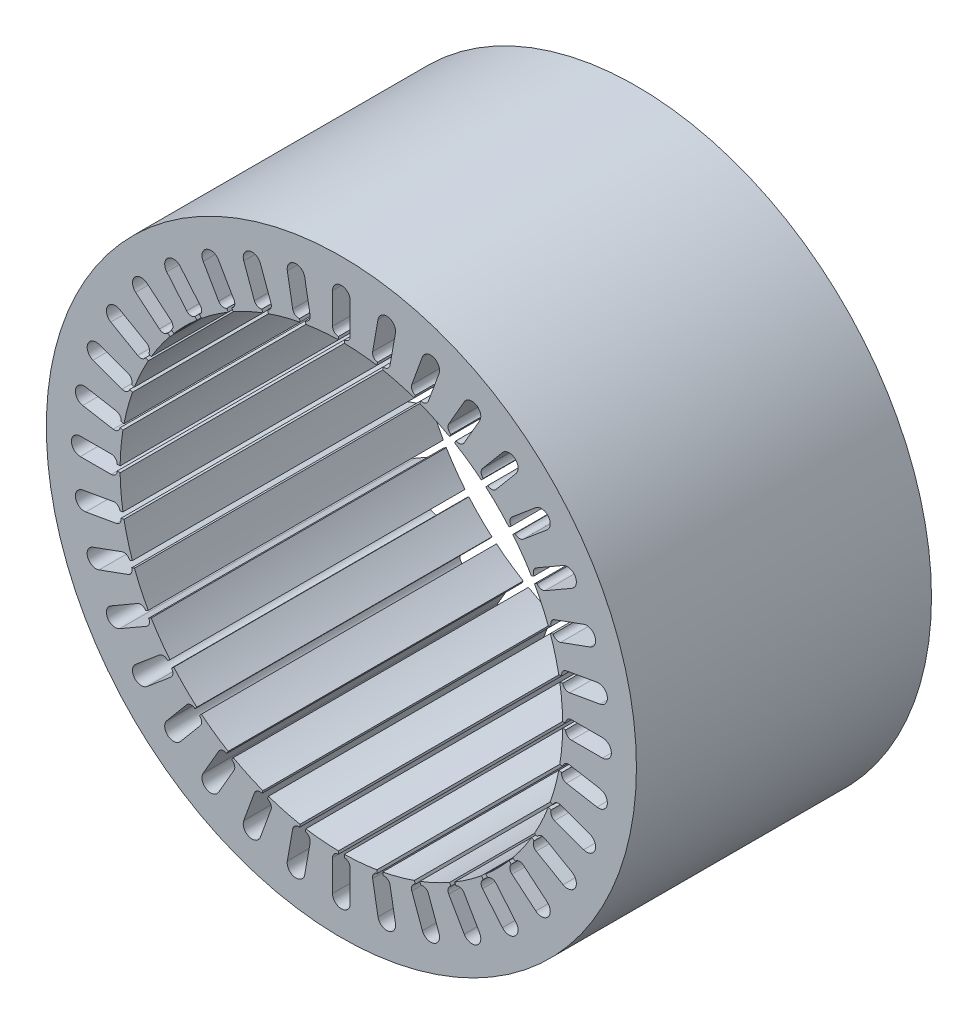
SolidWorks part; units mm, degrees
ref_plane "Front Plane" through (0, 0, 0) normal (0, 0, 1) x (1, 0, 0)
ref_plane "Top Plane" through (0, 0, 0) normal (0, 1, 0) x (1, 0, 0)
ref_plane "Right Plane" through (0, 0, 0) normal (1, 0, 0) x (0, 0, -1)
sketch "Sketch1" plane through (0, 0, 0) normal (0, 0, 1) x (1, 0, 0)
  line L0 (0, 0) -> (98.434, 0) construction
  line L1 (74.0277, -12.0376) -> (75.0125, -12.2113)
  line L2 (77.3294, -10.589) -> (87.6699, -12.4123)
  line L3 (76.2875, -16.4978) -> (86.628, -18.3211)
  line L4 (73.6804, -14.0073) -> (74.6652, -14.1809)
  line L5 (70.8127, -24.7095) -> (71.7524, -25.0516)
  line L6 (74.3158, -23.8562) -> (84.1826, -27.4474)
  line L7 (0, 0) -> (98.8022, 8.6441) construction
  line L8 (74.9933, 1) -> (75.9933, 1)
  line L9 (77.9933, 3) -> (88.4933, 3)
  line L10 (77.9933, -3) -> (88.4933, -3)
  line L11 (74.9933, -1) -> (75.9933, -1)
  line L12 (72.2637, -29.4944) -> (82.1305, -33.0856)
  line L13 (70.1287, -26.5889) -> (71.0684, -26.9309)
  line L14 (65.4461, -36.6306) -> (66.3122, -37.1306)
  line L15 (69.0442, -36.3986) -> (78.1375, -41.6486)
  line L16 (66.0442, -41.5947) -> (75.1375, -46.8447)
  line L17 (64.4461, -38.3627) -> (65.3122, -38.8627)
  line L18 (58.091, -47.4387) -> (58.8571, -48.0815)
  line L19 (61.6747, -47.835) -> (69.7182, -54.5843)
  line L20 (57.818, -52.4313) -> (65.8615, -59.1806)
  line L21 (56.8054, -48.9708) -> (57.5715, -49.6136)
  line L22 (48.9708, -56.8054) -> (49.6136, -57.5715)
  line L23 (52.4313, -57.818) -> (59.1806, -65.8615)
  line L24 (47.835, -61.6747) -> (54.5843, -69.7182)
  line L25 (47.4387, -58.091) -> (48.0815, -58.8571)
  line L26 (38.3627, -64.4461) -> (38.8627, -65.3122)
  line L27 (41.5947, -66.0442) -> (46.8447, -75.1375)
  line L28 (36.3986, -69.0442) -> (41.6486, -78.1375)
  line L29 (36.6306, -65.4461) -> (37.1306, -66.3122)
  line L30 (26.5889, -70.1287) -> (26.9309, -71.0684)
  line L31 (29.4944, -72.2637) -> (33.0856, -82.1305)
  line L32 (23.8562, -74.3158) -> (27.4474, -84.1826)
  line L33 (24.7095, -70.8127) -> (25.0516, -71.7524)
  line L34 (14.0073, -73.6804) -> (14.1809, -74.6652)
  line L35 (16.4978, -76.2875) -> (18.3211, -86.628)
  line L36 (10.589, -77.3294) -> (12.4123, -87.6699)
  line L37 (12.0376, -74.0277) -> (12.2113, -75.0125)
  line L38 (1, -74.9933) -> (1, -75.9933)
  line L39 (3, -77.9933) -> (3, -88.4933)
  line L40 (-3, -77.9933) -> (-3, -88.4933)
  line L41 (-1, -74.9933) -> (-1, -75.9933)
  line L42 (-12.0376, -74.0277) -> (-12.2113, -75.0125)
  line L43 (-10.589, -77.3294) -> (-12.4123, -87.6699)
  line L44 (-16.4978, -76.2875) -> (-18.3211, -86.628)
  line L45 (-14.0073, -73.6804) -> (-14.1809, -74.6652)
  line L46 (-24.7095, -70.8127) -> (-25.0516, -71.7524)
  line L47 (-23.8562, -74.3158) -> (-27.4474, -84.1826)
  line L48 (-29.4944, -72.2637) -> (-33.0856, -82.1305)
  line L49 (-26.5889, -70.1287) -> (-26.9309, -71.0684)
  line L50 (-36.6306, -65.4461) -> (-37.1306, -66.3122)
  line L51 (-36.3986, -69.0442) -> (-41.6486, -78.1375)
  line L52 (-41.5947, -66.0442) -> (-46.8447, -75.1375)
  line L53 (-38.3627, -64.4461) -> (-38.8627, -65.3122)
  line L54 (-47.4387, -58.091) -> (-48.0815, -58.8571)
  line L55 (-47.835, -61.6747) -> (-54.5843, -69.7182)
  line L56 (-52.4313, -57.818) -> (-59.1806, -65.8615)
  line L57 (-48.9708, -56.8054) -> (-49.6136, -57.5715)
  line L58 (-56.8054, -48.9708) -> (-57.5715, -49.6136)
  line L59 (-57.818, -52.4313) -> (-65.8615, -59.1806)
  line L60 (-61.6747, -47.835) -> (-69.7182, -54.5843)
  line L61 (-58.091, -47.4387) -> (-58.8571, -48.0815)
  line L62 (-64.4461, -38.3627) -> (-65.3122, -38.8627)
  line L63 (-66.0442, -41.5947) -> (-75.1375, -46.8447)
  line L64 (-69.0442, -36.3986) -> (-78.1375, -41.6486)
  line L65 (-65.4461, -36.6306) -> (-66.3122, -37.1306)
  line L66 (-70.1287, -26.5889) -> (-71.0684, -26.9309)
  line L67 (-72.2637, -29.4944) -> (-82.1305, -33.0856)
  line L68 (-74.3158, -23.8562) -> (-84.1826, -27.4474)
  line L69 (-70.8127, -24.7095) -> (-71.7524, -25.0516)
  line L70 (-73.6804, -14.0073) -> (-74.6652, -14.1809)
  line L71 (-76.2875, -16.4978) -> (-86.628, -18.3211)
  line L72 (-77.3294, -10.589) -> (-87.6699, -12.4123)
  line L73 (-74.0277, -12.0376) -> (-75.0125, -12.2113)
  line L74 (-74.9933, -1) -> (-75.9933, -1)
  line L75 (-77.9933, -3) -> (-88.4933, -3)
  line L76 (-77.9933, 3) -> (-88.4933, 3)
  line L77 (-74.9933, 1) -> (-75.9933, 1)
  line L78 (-74.0277, 12.0376) -> (-75.0125, 12.2113)
  line L79 (-77.3294, 10.589) -> (-87.6699, 12.4123)
  line L80 (-76.2875, 16.4978) -> (-86.628, 18.3211)
  line L81 (-73.6804, 14.0073) -> (-74.6652, 14.1809)
  line L82 (-70.8127, 24.7095) -> (-71.7524, 25.0516)
  line L83 (-74.3158, 23.8562) -> (-84.1826, 27.4474)
  line L84 (-72.2637, 29.4944) -> (-82.1305, 33.0856)
  line L85 (-70.1287, 26.5889) -> (-71.0684, 26.9309)
  line L86 (-65.4461, 36.6306) -> (-66.3122, 37.1306)
  line L87 (-69.0442, 36.3986) -> (-78.1375, 41.6486)
  line L88 (-66.0442, 41.5947) -> (-75.1375, 46.8447)
  line L89 (-64.4461, 38.3627) -> (-65.3122, 38.8627)
  line L90 (-58.091, 47.4387) -> (-58.8571, 48.0815)
  line L91 (-61.6747, 47.835) -> (-69.7182, 54.5843)
  line L92 (-57.818, 52.4313) -> (-65.8615, 59.1806)
  line L93 (-56.8054, 48.9708) -> (-57.5715, 49.6136)
  line L94 (-48.9708, 56.8054) -> (-49.6136, 57.5715)
  line L95 (-52.4313, 57.818) -> (-59.1806, 65.8615)
  line L96 (-47.835, 61.6747) -> (-54.5843, 69.7182)
  line L97 (-47.4387, 58.091) -> (-48.0815, 58.8571)
  line L98 (-38.3627, 64.4461) -> (-38.8627, 65.3122)
  line L99 (-41.5947, 66.0442) -> (-46.8447, 75.1375)
  line L100 (-36.3986, 69.0442) -> (-41.6486, 78.1375)
  line L101 (-36.6306, 65.4461) -> (-37.1306, 66.3122)
  line L102 (-26.5889, 70.1287) -> (-26.9309, 71.0684)
  line L103 (-29.4944, 72.2637) -> (-33.0856, 82.1305)
  line L104 (-23.8562, 74.3158) -> (-27.4474, 84.1826)
  line L105 (-24.7095, 70.8127) -> (-25.0516, 71.7524)
  line L106 (-14.0073, 73.6804) -> (-14.1809, 74.6652)
  line L107 (-16.4978, 76.2875) -> (-18.3211, 86.628)
  line L108 (-10.589, 77.3294) -> (-12.4123, 87.6699)
  line L109 (-12.0376, 74.0277) -> (-12.2113, 75.0125)
  line L110 (-1, 74.9933) -> (-1, 75.9933)
  line L111 (-3, 77.9933) -> (-3, 88.4933)
  line L112 (3, 77.9933) -> (3, 88.4933)
  line L113 (1, 74.9933) -> (1, 75.9933)
  line L114 (12.0376, 74.0277) -> (12.2113, 75.0125)
  line L115 (10.589, 77.3294) -> (12.4123, 87.6699)
  line L116 (16.4978, 76.2875) -> (18.3211, 86.628)
  line L117 (14.0073, 73.6804) -> (14.1809, 74.6652)
  line L118 (24.7095, 70.8127) -> (25.0516, 71.7524)
  line L119 (23.8562, 74.3158) -> (27.4474, 84.1826)
  line L120 (29.4944, 72.2637) -> (33.0856, 82.1305)
  line L121 (26.5889, 70.1287) -> (26.9309, 71.0684)
  line L122 (36.6306, 65.4461) -> (37.1306, 66.3122)
  line L123 (36.3986, 69.0442) -> (41.6486, 78.1375)
  line L124 (41.5947, 66.0442) -> (46.8447, 75.1375)
  line L125 (38.3627, 64.4461) -> (38.8627, 65.3122)
  line L126 (47.4387, 58.091) -> (48.0815, 58.8571)
  line L127 (47.835, 61.6747) -> (54.5843, 69.7182)
  line L128 (52.4313, 57.818) -> (59.1806, 65.8615)
  line L129 (48.9708, 56.8054) -> (49.6136, 57.5715)
  line L130 (56.8054, 48.9708) -> (57.5715, 49.6136)
  line L131 (57.818, 52.4313) -> (65.8615, 59.1806)
  line L132 (61.6747, 47.835) -> (69.7182, 54.5843)
  line L133 (58.091, 47.4387) -> (58.8571, 48.0815)
  line L134 (64.4461, 38.3627) -> (65.3122, 38.8627)
  line L135 (66.0442, 41.5947) -> (75.1375, 46.8447)
  line L136 (69.0442, 36.3986) -> (78.1375, 41.6486)
  line L137 (65.4461, 36.6306) -> (66.3122, 37.1306)
  line L138 (70.1287, 26.5889) -> (71.0684, 26.9309)
  line L139 (72.2637, 29.4944) -> (82.1305, 33.0856)
  line L140 (74.3158, 23.8562) -> (84.1826, 27.4474)
  line L141 (70.8127, 24.7095) -> (71.7524, 25.0516)
  line L142 (73.6804, 14.0073) -> (74.6652, 14.1809)
  line L143 (76.2875, 16.4978) -> (86.628, 18.3211)
  line L144 (77.3294, 10.589) -> (87.6699, 12.4123)
  line L145 (74.0277, 12.0376) -> (75.0125, 12.2113)
  arc A0 (75.9933, 1) -> (77.9933, 3) centre (77.9933, 1) cw
  arc A1 (88.4933, 3) -> (88.4933, -3) centre (88.4933, 0) cw
  arc A2 (75.9933, -1) -> (77.9933, -3) centre (77.9933, -1) ccw
  arc A3 (74.9933, 1) -> (74.7146, 6.5367) centre (0, 0) ccw
  arc A4 (74.9933, -1) -> (74.7146, -6.5367) centre (0, 0) cw
  arc A5 (74.0277, -12.0376) -> (74.7146, -6.5367) centre (0, 0) ccw
  arc A6 (75.0125, -12.2113) -> (77.3294, -10.589) centre (76.9821, -12.5586) cw
  arc A7 (87.6699, -12.4123) -> (86.628, -18.3211) centre (87.1489, -15.3667) cw
  arc A8 (74.6652, -14.1809) -> (76.2875, -16.4978) centre (76.6348, -14.5282) ccw
  arc A9 (73.6804, -14.0073) -> (72.4444, -19.4114) centre (0, 0) cw
  arc A10 (70.8127, -24.7095) -> (72.4444, -19.4114) centre (0, 0) ccw
  arc A11 (71.7524, -25.0516) -> (74.3158, -23.8562) centre (73.6318, -25.7356) cw
  arc A12 (84.1826, -27.4474) -> (82.1305, -33.0856) centre (83.1565, -30.2665) cw
  arc A13 (71.0684, -26.9309) -> (72.2637, -29.4944) centre (72.9477, -27.615) ccw
  arc A14 (70.1287, -26.5889) -> (67.9731, -31.6964) centre (0, 0) cw
  arc A15 (65.4461, -36.6306) -> (67.9731, -31.6964) centre (0, 0) ccw
  arc A16 (66.3122, -37.1306) -> (69.0442, -36.3986) centre (68.0442, -38.1306) cw
  arc A17 (78.1375, -41.6486) -> (75.1375, -46.8447) centre (76.6375, -44.2467) cw
  arc A18 (65.3122, -38.8627) -> (66.0442, -41.5947) centre (67.0442, -39.8627) ccw
  arc A19 (64.4461, -38.3627) -> (61.4364, -43.0182) centre (0, 0) cw
  arc A20 (58.091, -47.4387) -> (61.4364, -43.0182) centre (0, 0) ccw
  arc A21 (58.8571, -48.0815) -> (61.6747, -47.835) centre (60.3891, -49.3671) cw
  arc A22 (69.7182, -54.5843) -> (65.8615, -59.1806) centre (67.7898, -56.8824) cw
  arc A23 (57.5715, -49.6136) -> (57.818, -52.4313) centre (59.1036, -50.8992) ccw
  arc A24 (56.8054, -48.9708) -> (53.033, -53.033) centre (0, 0) cw
  arc A25 (48.9708, -56.8054) -> (53.033, -53.033) centre (0, 0) ccw
  arc A26 (49.6136, -57.5715) -> (52.4313, -57.818) centre (50.8992, -59.1036) cw
  arc A27 (59.1806, -65.8615) -> (54.5843, -69.7182) centre (56.8824, -67.7898) cw
  arc A28 (48.0815, -58.8571) -> (47.835, -61.6747) centre (49.3671, -60.3891) ccw
  arc A29 (47.4387, -58.091) -> (43.0182, -61.4364) centre (0, 0) cw
  arc A30 (38.3627, -64.4461) -> (43.0182, -61.4364) centre (0, 0) ccw
  arc A31 (38.8627, -65.3122) -> (41.5947, -66.0442) centre (39.8627, -67.0442) cw
  arc A32 (46.8447, -75.1375) -> (41.6486, -78.1375) centre (44.2467, -76.6375) cw
  arc A33 (37.1306, -66.3122) -> (36.3986, -69.0442) centre (38.1306, -68.0442) ccw
  arc A34 (36.6306, -65.4461) -> (31.6964, -67.9731) centre (0, 0) cw
  arc A35 (26.5889, -70.1287) -> (31.6964, -67.9731) centre (0, 0) ccw
  arc A36 (26.9309, -71.0684) -> (29.4944, -72.2637) centre (27.615, -72.9477) cw
  arc A37 (33.0856, -82.1305) -> (27.4474, -84.1826) centre (30.2665, -83.1565) cw
  arc A38 (25.0516, -71.7524) -> (23.8562, -74.3158) centre (25.7356, -73.6318) ccw
  arc A39 (24.7095, -70.8127) -> (19.4114, -72.4444) centre (0, 0) cw
  arc A40 (14.0073, -73.6804) -> (19.4114, -72.4444) centre (0, 0) ccw
  arc A41 (14.1809, -74.6652) -> (16.4978, -76.2875) centre (14.5282, -76.6348) cw
  arc A42 (18.3211, -86.628) -> (12.4123, -87.6699) centre (15.3667, -87.1489) cw
  arc A43 (12.2113, -75.0125) -> (10.589, -77.3294) centre (12.5586, -76.9821) ccw
  arc A44 (12.0376, -74.0277) -> (6.5367, -74.7146) centre (0, 0) cw
  arc A45 (1, -74.9933) -> (6.5367, -74.7146) centre (0, 0) ccw
  arc A46 (1, -75.9933) -> (3, -77.9933) centre (1, -77.9933) cw
  arc A47 (3, -88.4933) -> (-3, -88.4933) centre (0, -88.4933) cw
  arc A48 (-1, -75.9933) -> (-3, -77.9933) centre (-1, -77.9933) ccw
  arc A49 (-1, -74.9933) -> (-6.5367, -74.7146) centre (0, 0) cw
  arc A50 (-12.0376, -74.0277) -> (-6.5367, -74.7146) centre (0, 0) ccw
  arc A51 (-12.2113, -75.0125) -> (-10.589, -77.3294) centre (-12.5586, -76.9821) cw
  arc A52 (-12.4123, -87.6699) -> (-18.3211, -86.628) centre (-15.3667, -87.1489) cw
  arc A53 (-14.1809, -74.6652) -> (-16.4978, -76.2875) centre (-14.5282, -76.6348) ccw
  arc A54 (-14.0073, -73.6804) -> (-19.4114, -72.4444) centre (0, 0) cw
  arc A55 (-24.7095, -70.8127) -> (-19.4114, -72.4444) centre (0, 0) ccw
  arc A56 (-25.0516, -71.7524) -> (-23.8562, -74.3158) centre (-25.7356, -73.6318) cw
  arc A57 (-27.4474, -84.1826) -> (-33.0856, -82.1305) centre (-30.2665, -83.1565) cw
  arc A58 (-26.9309, -71.0684) -> (-29.4944, -72.2637) centre (-27.615, -72.9477) ccw
  arc A59 (-26.5889, -70.1287) -> (-31.6964, -67.9731) centre (0, 0) cw
  arc A60 (-36.6306, -65.4461) -> (-31.6964, -67.9731) centre (0, 0) ccw
  arc A61 (-37.1306, -66.3122) -> (-36.3986, -69.0442) centre (-38.1306, -68.0442) cw
  arc A62 (-41.6486, -78.1375) -> (-46.8447, -75.1375) centre (-44.2467, -76.6375) cw
  arc A63 (-38.8627, -65.3122) -> (-41.5947, -66.0442) centre (-39.8627, -67.0442) ccw
  arc A64 (-38.3627, -64.4461) -> (-43.0182, -61.4364) centre (0, 0) cw
  arc A65 (-47.4387, -58.091) -> (-43.0182, -61.4364) centre (0, 0) ccw
  arc A66 (-48.0815, -58.8571) -> (-47.835, -61.6747) centre (-49.3671, -60.3891) cw
  arc A67 (-54.5843, -69.7182) -> (-59.1806, -65.8615) centre (-56.8824, -67.7898) cw
  arc A68 (-49.6136, -57.5715) -> (-52.4313, -57.818) centre (-50.8992, -59.1036) ccw
  arc A69 (-48.9708, -56.8054) -> (-53.033, -53.033) centre (0, 0) cw
  arc A70 (-56.8054, -48.9708) -> (-53.033, -53.033) centre (0, 0) ccw
  arc A71 (-57.5715, -49.6136) -> (-57.818, -52.4313) centre (-59.1036, -50.8992) cw
  arc A72 (-65.8615, -59.1806) -> (-69.7182, -54.5843) centre (-67.7898, -56.8824) cw
  arc A73 (-58.8571, -48.0815) -> (-61.6747, -47.835) centre (-60.3891, -49.3671) ccw
  arc A74 (-58.091, -47.4387) -> (-61.4364, -43.0182) centre (0, 0) cw
  arc A75 (-64.4461, -38.3627) -> (-61.4364, -43.0182) centre (0, 0) ccw
  arc A76 (-65.3122, -38.8627) -> (-66.0442, -41.5947) centre (-67.0442, -39.8627) cw
  arc A77 (-75.1375, -46.8447) -> (-78.1375, -41.6486) centre (-76.6375, -44.2467) cw
  arc A78 (-66.3122, -37.1306) -> (-69.0442, -36.3986) centre (-68.0442, -38.1306) ccw
  arc A79 (-65.4461, -36.6306) -> (-67.9731, -31.6964) centre (0, 0) cw
  arc A80 (-70.1287, -26.5889) -> (-67.9731, -31.6964) centre (0, 0) ccw
  arc A81 (-71.0684, -26.9309) -> (-72.2637, -29.4944) centre (-72.9477, -27.615) cw
  arc A82 (-82.1305, -33.0856) -> (-84.1826, -27.4474) centre (-83.1565, -30.2665) cw
  arc A83 (-71.7524, -25.0516) -> (-74.3158, -23.8562) centre (-73.6318, -25.7356) ccw
  arc A84 (-70.8127, -24.7095) -> (-72.4444, -19.4114) centre (0, 0) cw
  arc A85 (-73.6804, -14.0073) -> (-72.4444, -19.4114) centre (0, 0) ccw
  arc A86 (-74.6652, -14.1809) -> (-76.2875, -16.4978) centre (-76.6348, -14.5282) cw
  arc A87 (-86.628, -18.3211) -> (-87.6699, -12.4123) centre (-87.1489, -15.3667) cw
  arc A88 (-75.0125, -12.2113) -> (-77.3294, -10.589) centre (-76.9821, -12.5586) ccw
  arc A89 (-74.0277, -12.0376) -> (-74.7146, -6.5367) centre (0, 0) cw
  arc A90 (-74.9933, -1) -> (-74.7146, -6.5367) centre (0, 0) ccw
  arc A91 (-75.9933, -1) -> (-77.9933, -3) centre (-77.9933, -1) cw
  arc A92 (-88.4933, -3) -> (-88.4933, 3) centre (-88.4933, 0) cw
  arc A93 (-75.9933, 1) -> (-77.9933, 3) centre (-77.9933, 1) ccw
  arc A94 (-74.9933, 1) -> (-74.7146, 6.5367) centre (0, 0) cw
  arc A95 (-74.0277, 12.0376) -> (-74.7146, 6.5367) centre (0, 0) ccw
  arc A96 (-75.0125, 12.2113) -> (-77.3294, 10.589) centre (-76.9821, 12.5586) cw
  arc A97 (-87.6699, 12.4123) -> (-86.628, 18.3211) centre (-87.1489, 15.3667) cw
  arc A98 (-74.6652, 14.1809) -> (-76.2875, 16.4978) centre (-76.6348, 14.5282) ccw
  arc A99 (-73.6804, 14.0073) -> (-72.4444, 19.4114) centre (0, 0) cw
  arc A100 (-70.8127, 24.7095) -> (-72.4444, 19.4114) centre (0, 0) ccw
  arc A101 (-71.7524, 25.0516) -> (-74.3158, 23.8562) centre (-73.6318, 25.7356) cw
  arc A102 (-84.1826, 27.4474) -> (-82.1305, 33.0856) centre (-83.1565, 30.2665) cw
  arc A103 (-71.0684, 26.9309) -> (-72.2637, 29.4944) centre (-72.9477, 27.615) ccw
  arc A104 (-70.1287, 26.5889) -> (-67.9731, 31.6964) centre (0, 0) cw
  arc A105 (-65.4461, 36.6306) -> (-67.9731, 31.6964) centre (0, 0) ccw
  arc A106 (-66.3122, 37.1306) -> (-69.0442, 36.3986) centre (-68.0442, 38.1306) cw
  arc A107 (-78.1375, 41.6486) -> (-75.1375, 46.8447) centre (-76.6375, 44.2467) cw
  arc A108 (-65.3122, 38.8627) -> (-66.0442, 41.5947) centre (-67.0442, 39.8627) ccw
  arc A109 (-64.4461, 38.3627) -> (-61.4364, 43.0182) centre (0, 0) cw
  arc A110 (-58.091, 47.4387) -> (-61.4364, 43.0182) centre (0, 0) ccw
  arc A111 (-58.8571, 48.0815) -> (-61.6747, 47.835) centre (-60.3891, 49.3671) cw
  arc A112 (-69.7182, 54.5843) -> (-65.8615, 59.1806) centre (-67.7898, 56.8824) cw
  arc A113 (-57.5715, 49.6136) -> (-57.818, 52.4313) centre (-59.1036, 50.8992) ccw
  arc A114 (-56.8054, 48.9708) -> (-53.033, 53.033) centre (0, 0) cw
  arc A115 (-48.9708, 56.8054) -> (-53.033, 53.033) centre (0, 0) ccw
  arc A116 (-49.6136, 57.5715) -> (-52.4313, 57.818) centre (-50.8992, 59.1036) cw
  arc A117 (-59.1806, 65.8615) -> (-54.5843, 69.7182) centre (-56.8824, 67.7898) cw
  arc A118 (-48.0815, 58.8571) -> (-47.835, 61.6747) centre (-49.3671, 60.3891) ccw
  arc A119 (-47.4387, 58.091) -> (-43.0182, 61.4364) centre (0, 0) cw
  arc A120 (-38.3627, 64.4461) -> (-43.0182, 61.4364) centre (0, 0) ccw
  arc A121 (-38.8627, 65.3122) -> (-41.5947, 66.0442) centre (-39.8627, 67.0442) cw
  arc A122 (-46.8447, 75.1375) -> (-41.6486, 78.1375) centre (-44.2467, 76.6375) cw
  arc A123 (-37.1306, 66.3122) -> (-36.3986, 69.0442) centre (-38.1306, 68.0442) ccw
  arc A124 (-36.6306, 65.4461) -> (-31.6964, 67.9731) centre (0, 0) cw
  arc A125 (-26.5889, 70.1287) -> (-31.6964, 67.9731) centre (0, 0) ccw
  arc A126 (-26.9309, 71.0684) -> (-29.4944, 72.2637) centre (-27.615, 72.9477) cw
  arc A127 (-33.0856, 82.1305) -> (-27.4474, 84.1826) centre (-30.2665, 83.1565) cw
  arc A128 (-25.0516, 71.7524) -> (-23.8562, 74.3158) centre (-25.7356, 73.6318) ccw
  arc A129 (-24.7095, 70.8127) -> (-19.4114, 72.4444) centre (0, 0) cw
  arc A130 (-14.0073, 73.6804) -> (-19.4114, 72.4444) centre (0, 0) ccw
  arc A131 (-14.1809, 74.6652) -> (-16.4978, 76.2875) centre (-14.5282, 76.6348) cw
  arc A132 (-18.3211, 86.628) -> (-12.4123, 87.6699) centre (-15.3667, 87.1489) cw
  arc A133 (-12.2113, 75.0125) -> (-10.589, 77.3294) centre (-12.5586, 76.9821) ccw
  arc A134 (-12.0376, 74.0277) -> (-6.5367, 74.7146) centre (0, 0) cw
  arc A135 (-1, 74.9933) -> (-6.5367, 74.7146) centre (0, 0) ccw
  arc A136 (-1, 75.9933) -> (-3, 77.9933) centre (-1, 77.9933) cw
  arc A137 (-3, 88.4933) -> (3, 88.4933) centre (0, 88.4933) cw
  arc A138 (1, 75.9933) -> (3, 77.9933) centre (1, 77.9933) ccw
  arc A139 (1, 74.9933) -> (6.5367, 74.7146) centre (0, 0) cw
  arc A140 (12.0376, 74.0277) -> (6.5367, 74.7146) centre (0, 0) ccw
  arc A141 (12.2113, 75.0125) -> (10.589, 77.3294) centre (12.5586, 76.9821) cw
  arc A142 (12.4123, 87.6699) -> (18.3211, 86.628) centre (15.3667, 87.1489) cw
  arc A143 (14.1809, 74.6652) -> (16.4978, 76.2875) centre (14.5282, 76.6348) ccw
  arc A144 (14.0073, 73.6804) -> (19.4114, 72.4444) centre (0, 0) cw
  arc A145 (24.7095, 70.8127) -> (19.4114, 72.4444) centre (0, 0) ccw
  arc A146 (25.0516, 71.7524) -> (23.8562, 74.3158) centre (25.7356, 73.6318) cw
  arc A147 (27.4474, 84.1826) -> (33.0856, 82.1305) centre (30.2665, 83.1565) cw
  arc A148 (26.9309, 71.0684) -> (29.4944, 72.2637) centre (27.615, 72.9477) ccw
  arc A149 (26.5889, 70.1287) -> (31.6964, 67.9731) centre (0, 0) cw
  arc A150 (36.6306, 65.4461) -> (31.6964, 67.9731) centre (0, 0) ccw
  arc A151 (37.1306, 66.3122) -> (36.3986, 69.0442) centre (38.1306, 68.0442) cw
  arc A152 (41.6486, 78.1375) -> (46.8447, 75.1375) centre (44.2467, 76.6375) cw
  arc A153 (38.8627, 65.3122) -> (41.5947, 66.0442) centre (39.8627, 67.0442) ccw
  arc A154 (38.3627, 64.4461) -> (43.0182, 61.4364) centre (0, 0) cw
  arc A155 (47.4387, 58.091) -> (43.0182, 61.4364) centre (0, 0) ccw
  arc A156 (48.0815, 58.8571) -> (47.835, 61.6747) centre (49.3671, 60.3891) cw
  arc A157 (54.5843, 69.7182) -> (59.1806, 65.8615) centre (56.8824, 67.7898) cw
  arc A158 (49.6136, 57.5715) -> (52.4313, 57.818) centre (50.8992, 59.1036) ccw
  arc A159 (48.9708, 56.8054) -> (53.033, 53.033) centre (0, 0) cw
  arc A160 (56.8054, 48.9708) -> (53.033, 53.033) centre (0, 0) ccw
  arc A161 (57.5715, 49.6136) -> (57.818, 52.4313) centre (59.1036, 50.8992) cw
  arc A162 (65.8615, 59.1806) -> (69.7182, 54.5843) centre (67.7898, 56.8824) cw
  arc A163 (58.8571, 48.0815) -> (61.6747, 47.835) centre (60.3891, 49.3671) ccw
  arc A164 (58.091, 47.4387) -> (61.4364, 43.0182) centre (0, 0) cw
  arc A165 (64.4461, 38.3627) -> (61.4364, 43.0182) centre (0, 0) ccw
  arc A166 (65.3122, 38.8627) -> (66.0442, 41.5947) centre (67.0442, 39.8627) cw
  arc A167 (75.1375, 46.8447) -> (78.1375, 41.6486) centre (76.6375, 44.2467) cw
  arc A168 (66.3122, 37.1306) -> (69.0442, 36.3986) centre (68.0442, 38.1306) ccw
  arc A169 (65.4461, 36.6306) -> (67.9731, 31.6964) centre (0, 0) cw
  arc A170 (70.1287, 26.5889) -> (67.9731, 31.6964) centre (0, 0) ccw
  arc A171 (71.0684, 26.9309) -> (72.2637, 29.4944) centre (72.9477, 27.615) cw
  arc A172 (82.1305, 33.0856) -> (84.1826, 27.4474) centre (83.1565, 30.2665) cw
  arc A173 (71.7524, 25.0516) -> (74.3158, 23.8562) centre (73.6318, 25.7356) ccw
  arc A174 (70.8127, 24.7095) -> (72.4444, 19.4114) centre (0, 0) cw
  arc A175 (73.6804, 14.0073) -> (72.4444, 19.4114) centre (0, 0) ccw
  arc A176 (74.6652, 14.1809) -> (76.2875, 16.4978) centre (76.6348, 14.5282) cw
  arc A177 (86.628, 18.3211) -> (87.6699, 12.4123) centre (87.1489, 15.3667) cw
  arc A178 (75.0125, 12.2113) -> (77.3294, 10.589) centre (76.9821, 12.5586) ccw
  arc A179 (74.0277, 12.0376) -> (74.7146, 6.5367) centre (0, 0) cw
  circle A180 centre (0, 0) radius 100
  point P475 (0, 0)
  dimension "D5" = 75
  dimension "D8" = 2
  dimension "D9" = 10.5
  dimension "D2" = 200
  dimension "D1" = 36
  dimension "D3" = 5
  dimension "D6" = 1
  dimension "D7" = 1
extrude "Boss-Extrude1" add sketch "Sketch1" along normal blind 100 contours A180 L145 A179 A3 L8 A0 L9 A1 L10 A2 L11 A4 A5 L1 A6 L2 A7 L3 A8 L4 A9 A10 L5 A11 L6 A12 L12 A13 L13 A14 A15 L14 A16 L15 A17 L16 A18 L17 A19 A20 L18 A21 L19 A22 L20 A23 L21 A24 A25 L22
